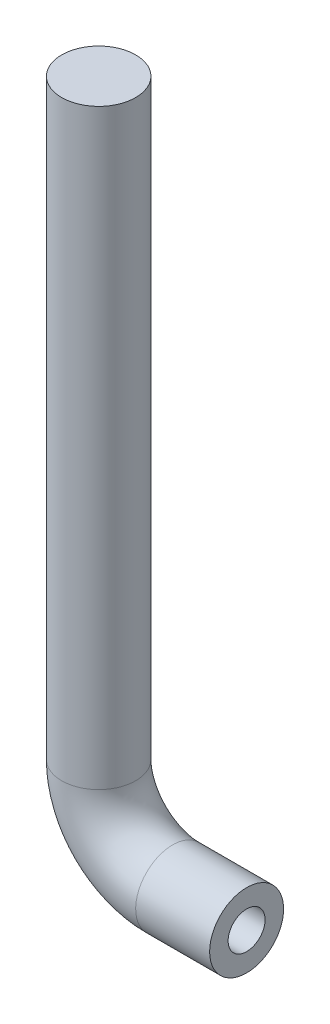
SolidWorks part; units mm, degrees
ref_plane "Front Plane" through (0, 0, 0) normal (0, 0, 1) x (1, 0, 0)
ref_plane "Top Plane" through (0, 0, 0) normal (0, 1, 0) x (1, 0, 0)
ref_plane "Right Plane" through (0, 0, 0) normal (1, 0, 0) x (0, 0, -1)
sketch "Sketch1" plane through (0, 0, 0) normal (0, 1, 0) x (1, 0, 0)
  circle A0 centre (0, 0) radius 6.35
  dimension "D1" = 12.7
sketch "Sketch2" plane through (0, 0, 0) normal (0, 0, 1) x (1, 0, 0)
  line L0 (0, 0) -> (0, -101.6)
  line L1 (6.35, 0) -> (-6.35, 0) construction
  line L2 (12.7, -114.3) -> (25.4, -114.3)
  arc A0 (0, -101.6) -> (12.7, -114.3) centre (12.7, -101.6) ccw
  dimension "D2" = 12.7
  dimension "D1" = 101.6
  dimension "D3" = 12.7
sweep "Sweep1" add profiles "Sketch1" path "Sketch2"
sketch "Sketch3" plane through (25.4, 0, 0) normal (1, 0, 0) x (0, 0, -1)
  circle A0 centre (0, -114.3) radius 3.175
  dimension "D1" = 6.35
extrude "Cut-Extrude1" cut sketch "Sketch3" against normal blind 6.35
